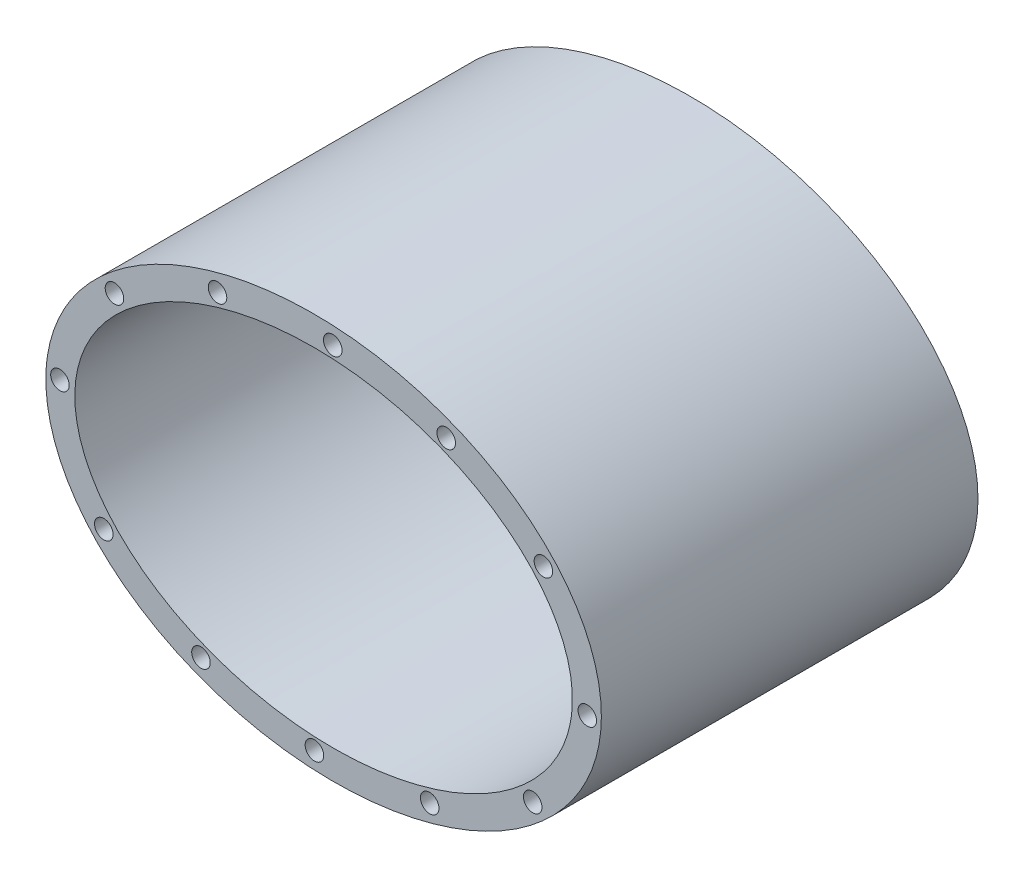
SolidWorks part; units mm, degrees
ref_plane "Front Plane" through (0, 0, 0) normal (0, 0, 1) x (1, 0, 0)
ref_plane "Top Plane" through (0, 0, 0) normal (0, 1, 0) x (1, 0, 0)
ref_plane "Right Plane" through (0, 0, 0) normal (1, 0, 0) x (0, 0, -1)
sketch "Sketch4" plane through (0, 0, 0) normal (0, 0, 1) x (1, 0, 0)
  ellipse E0 centre (0, 0) end of major axis (-30.4202, 1.5508) minor radius 21.634
extrude "Boss-Extrude3" add sketch "Sketch4" along normal mid plane 41.275
shell "Shell2" thickness 3.175
sketch "Sketch5" plane through (0, 0, 20.6375) normal (0, 0, 1) x (1, 0, 0)
  circle A0 centre (-28.8956, 1.4731) radius 1.016
  circle A1 centre (1.006, 19.7325) radius 1.016
  circle A2 centre (28.8956, -1.4731) radius 1.016
  circle A3 centre (-1.006, -19.7325) radius 1.016
  circle A5 centre (-11.6259, 18.4189) radius 1.016
  circle A6 centre (-22.9171, 12.6779) radius 1.016
  circle A8 centre (13.4388, 17.1411) radius 1.016
  circle A10 centre (24.0876, 10.2816) radius 1.016
  circle A11 centre (22.9171, -12.6779) radius 1.016
  circle A13 centre (11.6259, -18.4189) radius 1.016
  circle A14 centre (-24.0876, -10.2816) radius 1.016
  circle A15 centre (-13.4388, -17.1411) radius 1.016
  ellipse E0 centre (0, 0) end of major axis (-28.8956, 1.4731) minor radius 19.7581 construction
  point P39 (0, 0)
  point P40 (0, 0)
  point P42 (-17.2099, 17.3522)
  dimension "D1" = 2.032
  dimension "D2" = 2.032
  dimension "D3" = 2.032
  dimension "D5" = 2.032
  dimension "D6" = 2.032
  dimension "D8" = 2.032
  dimension "D9" = 2.032
  dimension "D10" = 2.032
  dimension "D12" = 2.032
  dimension "D13" = 2.032
  dimension "D14" = 2.032
  dimension "D16" = 2.032
  dimension "D17" = 12.7
  dimension "D4" = 12.7
  dimension "D7" = 12.7
  dimension "D11" = 12.7
  dimension "D15" = 12.7
  dimension "D18" = 12.7
  dimension "D19" = 12.7
  dimension "D20" = 12.7
extrude "Cut-Extrude1" cut sketch "Sketch5" against normal through all
equation "\"Radiusx\" = .08'Housing X radius"
equation "\"Bolt\"= 20'Bolt Count"
equation "\"Outside\"= 5 / 8 + 1"
equation "\"Inside\"= 3 / 8"
equation "\"D1@Boss-Extrude3\"=\"Outside\""
equation "\"D1@Sketch5\"=\"Radiusx\""
equation "\"D2@Sketch5\"=\"Radiusx\""
equation "\"D3@Sketch5\"=\"Radiusx\""
equation "\"D5@Sketch5\"=\"Radiusx\""
equation "\"D6@Sketch5\"=\"Radiusx\""
equation "\"D8@Sketch5\"=\"Radiusx\""
equation "\"D9@Sketch5\"=\"Radiusx\""
equation "\"D10@Sketch5\"=\"Radiusx\""
equation "\"D12@Sketch5\"=\"Radiusx\""
equation "\"D13@Sketch5\"=\"Radiusx\""
equation "\"D14@Sketch5\"=\"Radiusx\""
equation "\"D16@Sketch5\"=\"Radiusx\""
